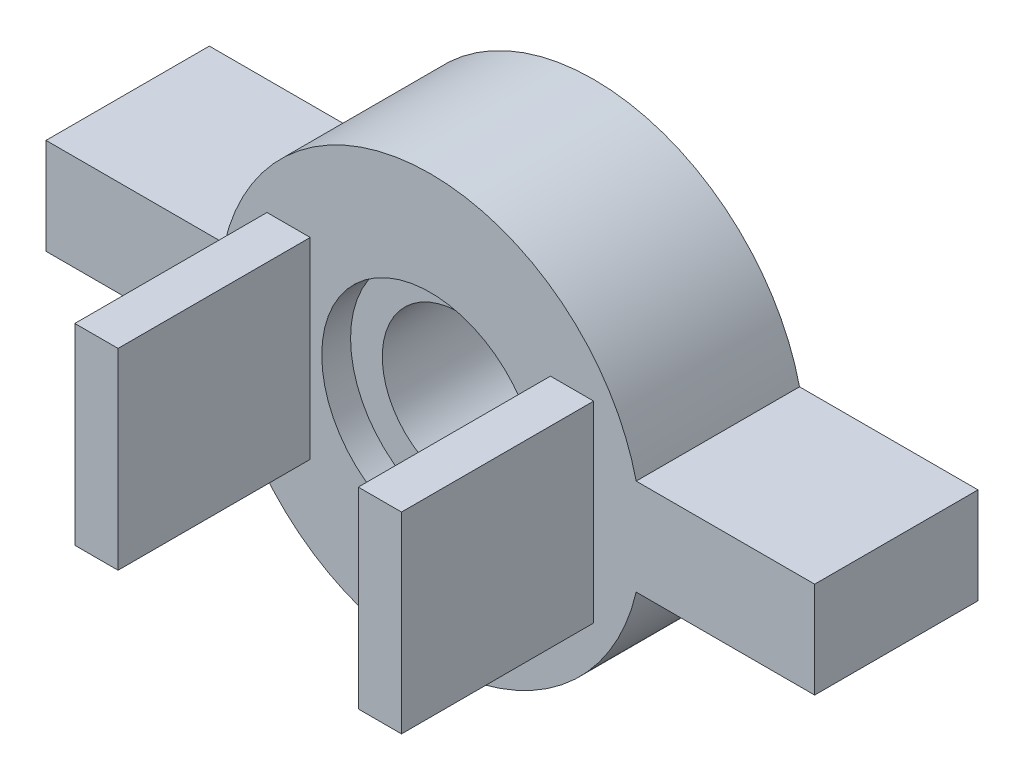
SolidWorks part; units mm, degrees
ref_plane "Front Plane" through (0, 0, 0) normal (0, 0, 1) x (1, 0, 0)
ref_plane "Top Plane" through (0, 0, 0) normal (0, 1, 0) x (1, 0, 0)
ref_plane "Right Plane" through (0, 0, 0) normal (1, 0, 0) x (0, 0, -1)
sketch "Sketch1" plane through (0, 0, 0) normal (0, 0, 1) x (1, 0, 0)
  line L0 (10.7121, 2.5) -> (20, 2.5)
  line L1 (-20, 2.5) -> (-10.7121, 2.5)
  line L2 (-20, 2.5) -> (-20, -2.5)
  line L3 (-20, -2.5) -> (-10.7121, -2.5)
  line L4 (20, 2.5) -> (20, -2.5)
  line L5 (-20, 2.5) -> (20, -2.5) construction
  line L6 (-20, -2.5) -> (20, 2.5) construction
  line L7 (10.7121, -2.5) -> (20, -2.5)
  arc A0 (-10.7121, -2.5) -> (10.7121, -2.5) centre (0, 0) ccw
  arc A1 (10.7121, 2.5) -> (-10.7121, 2.5) centre (0, 0) ccw
  dimension "D1" = 22
  dimension "D2" = 5
  dimension "D3" = 40
extrude "Boss-Extrude1" add sketch "Sketch1" along normal blind 8.5
sketch "Sketch2" plane through (0, 0, 8.5) normal (0, 0, 1) x (1, 0, 0)
  circle A0 centre (0, 0) radius 4
  dimension "D1" = 8
extrude "Cut-Extrude1" cut sketch "Sketch2" against normal up to next
sketch "Sketch3" plane through (0, 0, 8.5) normal (0, 0, 1) x (1, 0, 0)
  line L0 (6.25, 5) -> (8.5, 5)
  line L2 (-6.25, -5) -> (-6.25, 5)
  line L3 (6.25, -5) -> (8.5, -5)
  line L4 (6.25, -5) -> (6.25, 5)
  line L5 (-6.25, -5) -> (6.25, 5) construction
  line L6 (-6.25, 5) -> (6.25, -5) construction
  line L7 (-8.5, 5) -> (-6.25, 5)
  line L8 (-8.5, 5) -> (-8.5, -5)
  line L9 (-8.5, -5) -> (-6.25, -5)
  line L10 (8.5, 5) -> (8.5, -5)
  line L11 (-8.5, 5) -> (8.5, -5) construction
  line L12 (-8.5, -5) -> (8.5, 5) construction
  point P0 (0, 0)
  point P6 (0, 0)
  dimension "D1" = 12.5
  dimension "D2" = 10
  dimension "D3" = 17
extrude "Boss-Extrude3" add sketch "Sketch3" along normal blind 10
sketch "Sketch4" plane through (0, 0, 8.5) normal (0, 0, 1) x (1, 0, 0)
  circle A0 centre (0, 0) radius 5.65
  dimension "D1" = 11.3
extrude "Cut-Extrude2" cut sketch "Sketch4" against normal blind 1.5
